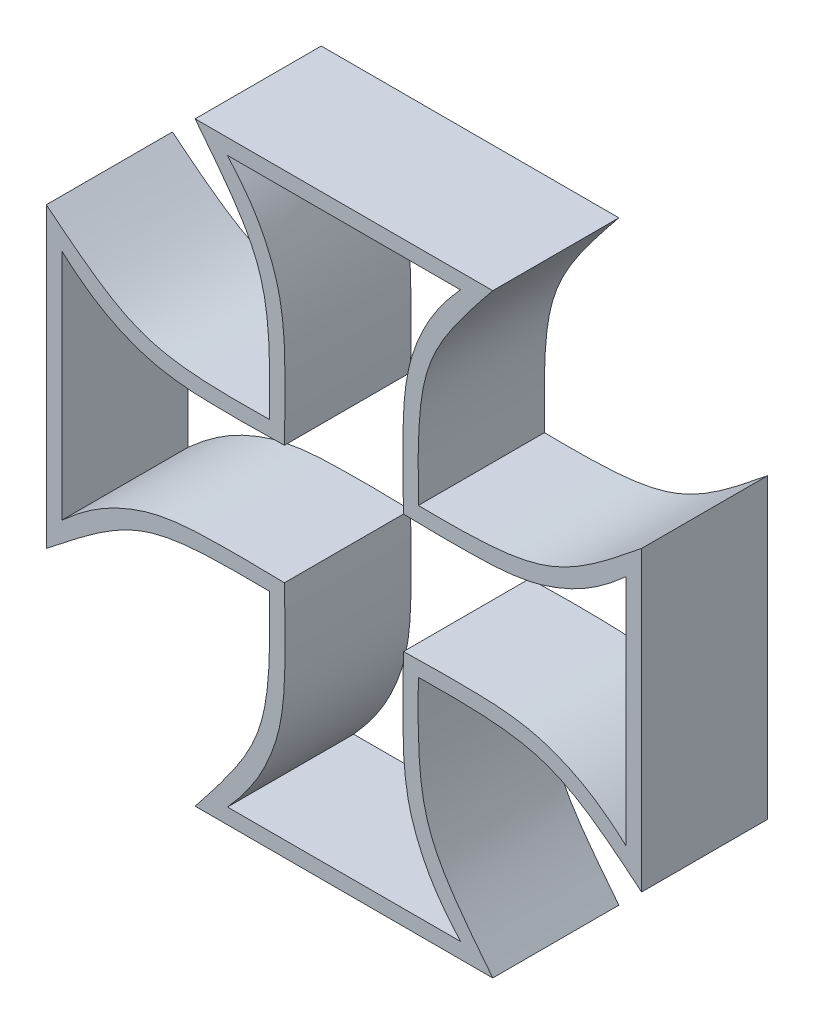
SolidWorks part; units mm, degrees
ref_plane "Front Plane" through (0, 0, 0) normal (0, 0, 1) x (1, 0, 0)
ref_plane "Top Plane" through (0, 0, 0) normal (0, 1, 0) x (1, 0, 0)
ref_plane "Right Plane" through (0, 0, 0) normal (1, 0, 0) x (0, 0, -1)
sketch "Sketch2" plane through (0, 0, 0) normal (0, 0, 1) x (1, 0, 0)
  line L0 (-13.367, 4.9838) -> (-13.3598, -13.4869)
  line L4 (-14.6037, -4.2523) -> (-14.6037, -16.0523)
  line L5 (-14.6037, -4.2523) -> (-14.6037, 7.5477)
  line L6 (8.9963, 19.3477) -> (-2.8037, 19.3477)
  line L7 (8.9963, 19.3477) -> (20.7963, 19.3477)
  line L8 (32.5963, -4.2523) -> (32.5963, 7.5477)
  line L9 (32.5963, -4.2523) -> (32.5963, -16.0523)
  line L10 (8.9963, -27.8523) -> (20.7963, -27.8523)
  line L11 (-2.8037, -27.8523) -> (8.9963, -27.8523)
  line L15 (-0.2356, -26.6278) -> (18.2351, -26.6206)
  line L16 (31.3608, -13.4882) -> (31.3536, 4.9825)
  line L17 (18.228, 18.1239) -> (-0.2427, 18.1167)
  spline S0 degree 3 poles (32.5963, -16.0523) (26.0757, -10.6367) (24.5075, -10.0216) (14.8963, -10.1523) knots 0 0 0 0 1 1 1 1
  spline S1 degree 3 poles (-2.8037, -27.8523) (2.7032, -20.9051) (3.227, -19.7635) (3.0963, -10.1523) knots 0 0 0 0 1 1 1 1
  spline S2 degree 3 poles (20.7963, -27.8523) (15.2894, -20.9051) (14.7656, -19.7635) (14.8963, -10.1523) knots 0 0 0 0 1 1 1 1
  spline S3 degree 3 poles (32.5963, 7.5477) (26.0602, 2.2045) (24.5075, 1.5171) (14.8963, 1.6477) knots 0 0 0 0 1 1 1 1
  spline S4 degree 3 poles (-14.6037, 7.5477) (-7.7785, 2.0577) (-6.5149, 1.5171) (3.0963, 1.6477) knots 0 0 0 0 1 1 1 1
  spline S5 degree 3 poles (-14.6037, -16.0523) (-7.6509, -10.5197) (-6.5149, -10.0216) (3.0963, -10.1523) knots 0 0 0 0 1 1 1 1
  spline S6 degree 3 poles (20.7963, 19.3477) (15.1779, 12.3852) (14.7656, 11.259) (14.8963, 1.6477) knots 0 0 0 0 1 1 1 1
  spline S7 degree 3 poles (-2.8037, 19.3477) (2.7032, 12.4006) (3.227, 11.259) (3.0963, 1.6477) knots 0 0 0 0 1 1 1 1
  spline S8 degree 3 poles (4.2763, -8.9723) (1.3571, -8.891) (-1.1076, -8.9389) (-3.6193, -8.9804) (-5.8246, -9.2806) (-9.5441, -10.538) (-11.4689, -11.7894) (-13.3598, -13.4869) knots 0 0 0 0 0.101134 0.143755 0.394825 0.483587 1 1 1 1
  spline S9 degree 3 poles (13.7163, -8.9723) (13.635, -11.8915) (13.688, -14.3707) (13.7267, -16.8746) (14.0291, -19.0859) (15.2858, -22.8037) (16.5376, -24.7297) (18.2351, -26.6206) knots 0 0 0 0 0.101134 0.143755 0.394825 0.483587 1 1 1 1
  spline S10 degree 3 poles (4.2763, 0.4677) (1.3571, 0.3865) (-1.1162, 0.4362) (-3.6233, 0.4766) (-5.8322, 0.7776) (-9.5507, 2.0348) (-11.4761, 3.2863) (-13.367, 4.9838) knots 0 0 0 0 0.101134 0.143755 0.394825 0.483587 1 1 1 1
  spline S11 degree 3 poles (4.2763, -8.9723) (4.3575, -11.8915) (4.3129, -14.3794) (4.2697, -16.8786) (3.9708, -19.0935) (2.7131, -22.8103) (1.4619, -24.7369) (-0.2356, -26.6278) knots 0 0 0 0 0.101134 0.143755 0.394825 0.483587 1 1 1 1
  spline S12 degree 3 poles (13.7163, 0.4677) (16.6355, 0.3865) (19.1015, 0.4346) (21.6125, 0.4759) (23.8184, 0.7762) (27.5378, 2.0336) (29.4627, 3.285) (31.3536, 4.9825) knots 0 0 0 0 0.101134 0.143755 0.394825 0.483587 1 1 1 1
  spline S13 degree 3 poles (13.7163, -8.9723) (16.6355, -8.891) (19.1102, -8.9405) (21.6165, -8.9811) (23.826, -9.282) (27.5443, -10.5392) (29.4699, -11.7907) (31.3608, -13.4882) knots 0 0 0 0 0.101134 0.143755 0.394825 0.483587 1 1 1 1
  spline S14 degree 3 poles (4.2763, 0.4677) (4.3575, 3.3869) (4.3044, 5.867) (4.2658, 8.3704) (3.9633, 10.5821) (2.7066, 14.2998) (1.4548, 16.2258) (-0.2427, 18.1167) knots 0 0 0 0 0.101134 0.143755 0.394825 0.483587 1 1 1 1
  spline S15 degree 3 poles (13.7163, 0.4677) (13.635, 3.3869) (13.6795, 5.8756) (13.7228, 8.3744) (14.0216, 10.5897) (15.2793, 14.3064) (16.5305, 16.233) (18.228, 18.1239) knots 0 0 0 0 0.101134 0.143755 0.394825 0.483587 1 1 1 1
  point P0 (8.9963, -4.2523)
extrude "Boss-Extrude2" add sketch "Sketch2" along normal blind 10
